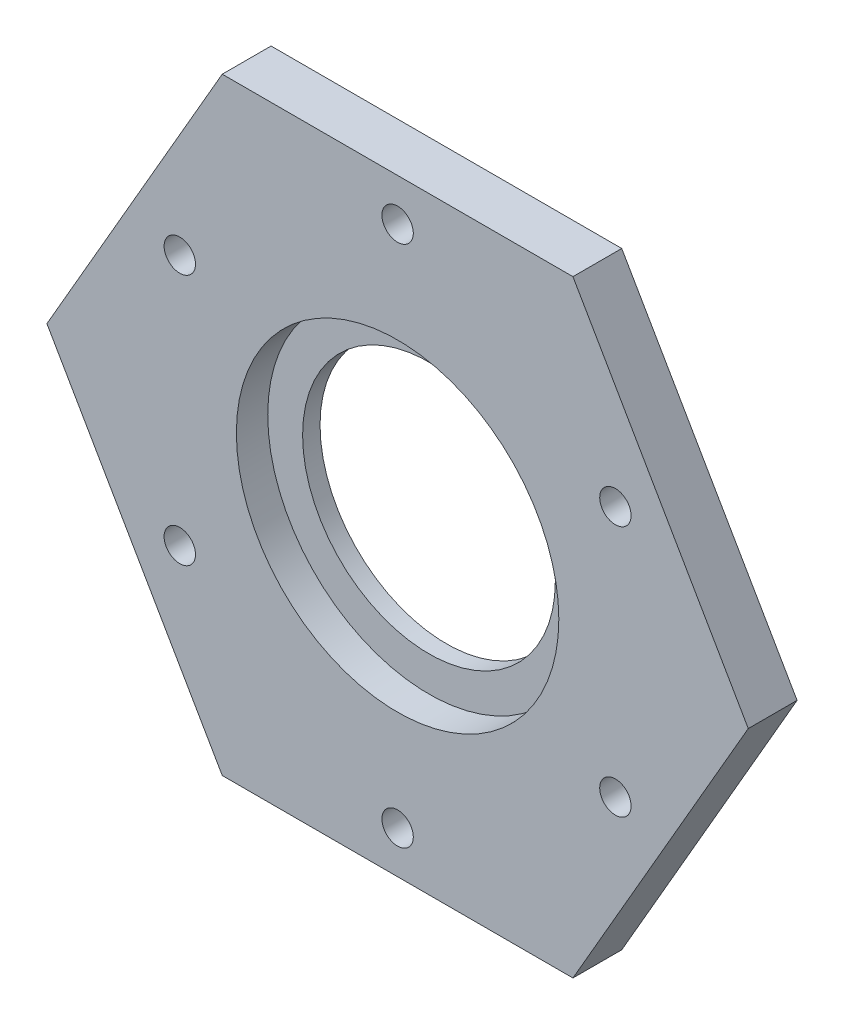
SolidWorks part; units mm, degrees
ref_plane "前视基准面" through (0, 0, 0) normal (0, 0, 1) x (1, 0, 0)
ref_plane "上视基准面" through (0, 0, 0) normal (0, 1, 0) x (1, 0, 0)
ref_plane "右视基准面" through (0, 0, 0) normal (1, 0, 0) x (0, 0, -1)
sketch "草图1" plane through (0, 0, 0) normal (0, 0, 1) x (1, 0, 0)
  line L0 (10.0594, 17.4234) -> (-10.0594, 17.4234)
  line L1 (15.5, 0) -> (7.75, 13.4234)
  line L2 (7.75, 13.4234) -> (-7.75, 13.4234)
  line L3 (-7.75, 13.4234) -> (-15.5, 0)
  line L4 (-15.5, 0) -> (-7.75, -13.4234)
  line L5 (-7.75, -13.4234) -> (7.75, -13.4234)
  line L6 (7.75, -13.4234) -> (15.5, 0)
  line L7 (-10.0594, 17.4234) -> (-20.1188, 0)
  line L8 (-20.1188, 0) -> (-10.0594, -17.4234)
  line L9 (-10.0594, -17.4234) -> (10.0594, -17.4234)
  line L10 (10.0594, -17.4234) -> (20.1188, 0)
  line L11 (20.1188, 0) -> (10.0594, 17.4234)
  circle A0 centre (0, 0) radius 13.4234 construction
  dimension "D1" = 15.5
  dimension "D2" = 4
extrude "凸台-拉伸1" add sketch "草图1" along normal blind 7
sketch "草图2" plane through (0, 0, 7) normal (0, 0, 1) x (1, 0, 0)
  line L0 (-5.5735, 13.4234) -> (-5.5735, 15.3499)
  line L1 (7.75, 13.4234) -> (-7.75, 13.4234) construction
  line L2 (-5.5735, 15.3499) -> (-4.8201, 16.0618)
  line L3 (5.5735, 13.4234) -> (5.5735, 15.3499)
  line L4 (0, 19.3164) -> (0, 10.8862) construction
  line L5 (5.5735, 15.3499) -> (4.8201, 16.0618)
  line L6 (-4.8201, 16.0618) -> (4.8201, 16.0618)
  line L7 (5.5735, 13.4234) -> (-5.5735, 13.4234)
  line L8 (0, -18.1349) -> (0, -9.4848) construction
  line L9 (6.8633, -13.4234) -> (6.8633, -16.4408)
  line L10 (-7.75, -13.4234) -> (7.75, -13.4234) construction
  line L11 (6.8633, -16.4408) -> (5.8807, -17.4234)
  line L12 (-10.0594, -17.4234) -> (10.0594, -17.4234) construction
  line L13 (-6.8633, -16.4408) -> (-5.8807, -17.4234)
  line L14 (-6.8633, -13.4234) -> (-6.8633, -16.4408)
  line L15 (-5.8807, -17.4234) -> (5.8807, -17.4234)
  line L16 (-6.8633, -13.4234) -> (6.8633, -13.4234)
  line M8 (-10.0594, -17.4234) -> (10.0594, -17.4234)
  line M12 (7.75, -13.4234) -> (-7.75, -13.4234)
extrude "切除-拉伸1" cut sketch "草图2" against normal blind 1.8 contours L14 L13 L11 L9 M12 M8 | L6 L5 L3 L7 L0 L2
sketch "草图3" plane through (0, 0, 7) normal (0, 0, 1) x (1, 0, 0)
  line L0 (8.4606, 12.1926) -> (11.9247, 14.1926)
  line L1 (15.5, 0) -> (7.75, 13.4234) construction
  line L2 (20.1188, 0) -> (10.0594, 17.4234) construction
  line L3 (11.9247, 14.1926) -> (18.4288, 2.9271)
  line L4 (18.4288, 2.9271) -> (14.9647, 0.9271)
  line L5 (14.9647, 0.9271) -> (8.4606, 12.1926)
extrude "切除-拉伸2" cut sketch "草图3" against normal blind 3
sketch "草图4" plane through (0, 0, 0) normal (0, 0, -1) x (-1, 0, 0)
  line L0 (-11.2456, -7.3688) -> (-6.3823, -7.3688)
  line L1 (-7.75, -13.4234) -> (-15.5, 0) construction
  line L2 (-6.3823, -7.3688) -> (-6.3823, -13.4234)
  line L3 (7.75, -13.4234) -> (-7.75, -13.4234) construction
  line L4 (-6.3823, -13.4234) -> (-7.75, -13.4234)
  line L5 (-7.75, -13.4234) -> (-11.2456, -7.3688)
  line L6 (6.1453, -7.3688) -> (11.2456, -7.3688)
  line L7 (15.5, 0) -> (7.75, -13.4234) construction
  line L8 (11.2456, -7.3688) -> (7.75, -13.4234)
  line L9 (7.75, -13.4234) -> (6.1453, -13.4234)
  line L10 (6.1453, -13.4234) -> (6.1453, -7.3688)
  line L11 (6.1453, 13.4234) -> (6.1453, 8.4885)
  line L12 (-7.75, 13.4234) -> (7.75, 13.4234) construction
  line L13 (6.1453, 8.4885) -> (10.5991, 8.4885)
  line L14 (7.75, 13.4234) -> (15.5, 0) construction
  line L15 (10.5991, 8.4885) -> (7.75, 13.4234)
  line L16 (7.75, 13.4234) -> (6.1453, 13.4234)
  line L17 (-8.4606, 12.1926) -> (-6.6742, 11.1612)
  line L19 (-6.6742, 11.1612) -> (-13.5028, -0.6663)
  line L20 (-13.5028, -0.6663) -> (-15.2892, 0.3651)
  line L21 (-15.5, 0) -> (-7.75, 13.4234) construction
  line L22 (-15.2892, 0.3651) -> (-8.4606, 12.1926)
extrude "凸台-拉伸4" add sketch "草图4" against normal blind 5.7 separate body
sketch "草图6" plane through (0, 0, 0) normal (0, 0, -1) x (-1, 0, 0)
  line L0 (-7.1671, 10.3074) -> (-6.1899, 10.3074)
  line L1 (-13.5028, -0.6663) -> (-6.6742, 11.1612) construction
  line L2 (-6.1899, 10.3074) -> (-6.1899, -5.9802)
  line L3 (-6.1899, -5.9802) -> (-12.0474, -5.9802)
  line L4 (-7.75, -13.4234) -> (-15.5, 0) construction
  line L7 (-15.5, 0) -> (-7.75, 13.4234) construction
  line L8 (-9.549, 10.3074) -> (-7.1671, 10.3074)
  line L9 (-5.839, 13.4234) -> (-5.839, 11.3427)
  line L10 (-7.75, 13.4234) -> (7.75, 13.4234) construction
  line L11 (-5.839, 11.3427) -> (5.7465, 11.3427)
  line L12 (5.7465, 11.3427) -> (5.7465, 13.4234)
  line L14 (6.1453, 7.2648) -> (6.1453, 3.9358)
  line L15 (6.1453, -5.9802) -> (12.0474, -5.9802)
  line L16 (15.5, 0) -> (7.75, -13.4234) construction
  line L20 (5.7465, 13.4234) -> (5.7465, 15.341)
  line L21 (5.7465, 15.341) -> (-5.839, 15.341)
  line L22 (-5.839, 15.341) -> (-5.839, 13.4234)
  line L23 (-9.549, 10.3074) -> (-11.4726, 10.3074)
  line L24 (-11.4726, 10.3074) -> (-17.3636, 0)
  line L25 (-17.3636, 0) -> (-13.6263, -5.9802)
  line L26 (-13.6263, -5.9802) -> (-12.0474, -5.9802)
  line L28 (12.8121, 7.2648) -> (14.8926, 3.9358)
  line L29 (17.3523, 0) -> (13.9344, -5.9802)
  line L30 (13.9344, -5.9802) -> (12.0474, -5.9802)
  line L31 (6.1453, 7.2648) -> (12.8121, 7.2648)
  line L32 (6.1453, 3.9358) -> (14.8926, 3.9358)
  line L33 (17.3523, 0) -> (6.1453, 0)
  line L34 (6.1453, 0) -> (6.1453, -5.9802)
extrude "凸台-拉伸21" add sketch "草图6" against normal blind 3.5 separate body
sketch "草图12" plane through (0, 0, 0) normal (0, 0, -1) x (-1, 0, 0)
  line L1 (-10.0594, 17.4234) -> (-20.1188, 0)
  line L2 (-20.1188, 0) -> (-10.0594, -17.4234)
  line L3 (-10.0594, -17.4234) -> (10.0594, -17.4234)
  line L4 (10.0594, -17.4234) -> (20.1188, 0)
  line L5 (20.1188, 0) -> (10.0594, 17.4234)
  line L6 (10.0594, 17.4234) -> (-10.0594, 17.4234)
  circle A0 centre (0, 0) radius 17.4234 construction
extrude "凸台-拉伸22" add sketch "草图12" along normal blind 1 separate body
sketch "草图13" plane through (0, 0, -1) normal (0, 0, -1) x (-1, 0, 0)
  line L0 (10.1234, 2.2395) -> (7.1359, 2.2395) construction
  line L1 (10.1234, 1.0625) -> (7.1359, 1.0625)
  line L2 (10.1234, 3.4166) -> (7.1359, 3.4166)
  line L3 (8.6297, 1.7395) -> (8.6297, 2.7395) construction
  arc A0 (10.1234, 1.0625) -> (10.1234, 3.4166) centre (10.1234, 2.2395) ccw
  arc A1 (7.1359, 3.4166) -> (7.1359, 1.0625) centre (7.1359, 2.2395) ccw
  point P2 (8.6297, 2.2395)
extrude "切除-拉伸3" cut sketch "草图13" against normal blind 10
sketch "草图14" plane through (0, 0, 5.7) normal (0, 0, 1) x (1, 0, 0)
  line L0 (-7.75, 13.4234) -> (-6.1453, 13.4234)
  line L1 (-6.1453, 13.4234) -> (-6.1453, 8.4635)
  line L2 (8.4603, 12.1924) -> (8.4603, 8.0675)
  line L3 (-7.75, 13.4234) -> (-10.5991, 8.4885)
  line L4 (-10.5991, 8.4885) -> (-6.1453, 8.4635)
  line L5 (6.6742, 11.1612) -> (8.4606, 12.1926) construction
  line L6 (13.5028, -0.6663) -> (6.6742, 11.1612) construction
  line L7 (8.4603, 8.0675) -> (6.6742, 11.1612)
  line L8 (6.6742, 11.1612) -> (8.4603, 12.1924)
extrude "切除-拉伸4" cut sketch "草图14" against normal blind 1.5
sketch "草图15" plane through (0, 0, 5.2) normal (0, 0, 1) x (1, 0, 0)
  line L0 (0, 17.0326) -> (0, 11.8468) construction
  line L1 (-2.4446, 16.0618) -> (-2.4446, 13.4234)
  line L2 (-4.8201, 16.0618) -> (4.8201, 16.0618) construction
  line L3 (5.5735, 13.4234) -> (-5.5735, 13.4234) construction
  line L4 (-2.4446, 13.4234) -> (-5.5735, 13.4234)
  line L5 (-5.5735, 13.4234) -> (-5.5735, 15.3499)
  line L6 (-5.5735, 15.3499) -> (-4.8201, 16.0618) construction
  line L7 (-5.5735, 15.3499) -> (-4.8201, 16.0618) construction
  line L8 (-5.5735, 15.3499) -> (-4.8201, 16.0618)
  line L9 (-4.8201, 16.0618) -> (-2.4446, 16.0618)
  line L10 (4.8201, 16.0618) -> (2.4446, 16.0618)
  line L11 (5.5735, 15.3499) -> (4.8201, 16.0618)
  line L12 (5.5735, 13.4234) -> (5.5735, 15.3499)
  line L13 (2.4446, 13.4234) -> (5.5735, 13.4234)
  line L14 (2.4446, 16.0618) -> (2.4446, 13.4234)
extrude "切除-拉伸5" cut sketch "草图15" against normal blind 1
sketch "草图16" plane through (0, 0, 7) normal (0, 0, 1) x (1, 0, 0)
  line L0 (7.75, 17.4234) -> (17.8094, 0)
  line L1 (10.0594, 17.4234) -> (-10.0594, 17.4234) construction
  line L2 (10.0594, -17.4234) -> (20.1188, 0) construction
  line L3 (20.1188, 0) -> (18.4288, 2.9271) construction
  line L4 (11.9247, 14.1926) -> (10.0594, 17.4234) construction
  line L5 (7.75, 17.4234) -> (10.0594, 17.4234)
  line L6 (10.0594, 17.4234) -> (20.1188, 0)
  line L7 (20.1188, 0) -> (18.9641, -2)
  line L8 (17.8094, 0) -> (7.75, -17.4234)
  line L9 (10.0594, -17.4234) -> (7.75, -17.4234)
  line L11 (18.9641, -2) -> (10.0594, -17.4234)
  line L12 (0, 18.7265) -> (0, -21.8829) construction
  line L13 (-18.9641, -2) -> (-10.0594, -17.4234)
  line L14 (-10.0594, -17.4234) -> (-7.75, -17.4234)
  line L15 (-17.8094, 0) -> (-7.75, -17.4234)
  line L16 (-20.1188, 0) -> (-18.9641, -2)
  line L17 (-10.0594, 17.4234) -> (-20.1188, 0)
  line L18 (-7.75, 17.4234) -> (-10.0594, 17.4234)
  line L19 (-7.75, 17.4234) -> (-17.8094, 0)
  dimension "D1" = 2
  dimension "D2" = 2
sketch "草图18" plane through (0, 0, 7) normal (0, 0, 1) x (1, 0, 0)
  line L0 (-4.8201, 16.0618) -> (-4.8201, 17.4234)
  line L1 (4.8201, 16.0618) -> (4.8201, 17.4234)
  line L2 (-4.8201, 17.4234) -> (-10.0594, 17.4234)
  line L9 (18.4288, 2.9271) -> (14.9647, 0.9271)
  line L10 (14.9647, 0.9271) -> (15.5, 0)
  line L11 (15.5, 0) -> (7.75, -13.4234)
  line L12 (7.75, -13.4234) -> (6.8633, -13.4234)
  line L13 (6.8633, -13.4234) -> (6.8633, -16.4408)
  line L14 (6.8633, -16.4408) -> (5.8807, -17.4234)
  line L15 (5.8807, -17.4234) -> (10.0594, -17.4234)
  line L16 (10.0594, -17.4234) -> (20.1188, 0)
  line L17 (20.1188, 0) -> (18.4288, 2.9271)
  line L18 (18.4288, 2.9271) -> (14.9647, 0.9271)
  line L19 (8.4606, 12.1926) -> (11.9247, 14.1926)
  line L20 (11.9247, 14.1926) -> (10.0594, 17.4234)
  line L21 (10.0594, 17.4234) -> (-10.0594, 17.4234)
  line L22 (-10.0594, 17.4234) -> (-20.1188, 0)
  line L23 (-20.1188, 0) -> (-10.0594, -17.4234)
  line L24 (-10.0594, -17.4234) -> (-5.8807, -17.4234)
  line L25 (-5.8807, -17.4234) -> (-6.8633, -16.4408)
  line L26 (-6.8633, -16.4408) -> (-6.8633, -13.4234)
  line L27 (-6.8633, -13.4234) -> (-7.75, -13.4234)
  line L28 (-7.75, -13.4234) -> (-15.5, 0)
  line L29 (-15.5, 0) -> (-7.75, 13.4234)
  line L30 (-7.75, 13.4234) -> (-5.5735, 13.4234)
  line L31 (-5.5735, 13.4234) -> (-5.5735, 15.3499)
  line L32 (-5.5735, 15.3499) -> (-4.8201, 16.0618)
  line L33 (-4.8201, 16.0618) -> (4.8201, 16.0618)
  line L34 (4.8201, 16.0618) -> (5.5735, 15.3499)
  line L35 (5.5735, 15.3499) -> (5.5735, 13.4234)
  line L36 (5.5735, 13.4234) -> (7.75, 13.4234)
  line L37 (7.75, 13.4234) -> (8.4606, 12.1926)
  line L38 (8.4606, 12.1926) -> (11.9247, 14.1926)
  line L39 (11.9247, 14.1926) -> (10.0594, 17.4234)
  line L40 (10.0594, 17.4234) -> (4.8201, 17.4234)
  line L41 (-10.0594, 17.4234) -> (-20.1188, 0)
  line L42 (-20.1188, 0) -> (-10.0594, -17.4234)
  line L43 (-10.0594, -17.4234) -> (-5.8807, -17.4234)
  line L44 (-5.8807, -17.4234) -> (-6.8633, -16.4408)
  line L45 (-6.8633, -16.4408) -> (-6.8633, -13.4234)
  line L46 (-6.8633, -13.4234) -> (-7.75, -13.4234)
  line L47 (-7.75, -13.4234) -> (-15.5, 0)
  line L48 (-15.5, 0) -> (-7.75, 13.4234)
  line L49 (-7.75, 13.4234) -> (-5.5735, 13.4234)
  line L50 (-5.5735, 13.4234) -> (-5.5735, 15.3499)
  line L51 (-5.5735, 15.3499) -> (-4.8201, 16.0618)
  line L53 (4.8201, 16.0618) -> (5.5735, 15.3499)
  line L54 (5.5735, 15.3499) -> (5.5735, 13.4234)
  line L55 (5.5735, 13.4234) -> (7.75, 13.4234)
  line L56 (7.75, 13.4234) -> (8.4606, 12.1926)
  line L57 (14.9647, 0.9271) -> (15.5, 0)
  line L58 (15.5, 0) -> (7.75, -13.4234)
  line L59 (7.75, -13.4234) -> (6.8633, -13.4234)
  line L60 (6.8633, -13.4234) -> (6.8633, -16.4408)
  line L61 (6.8633, -16.4408) -> (5.8807, -17.4234)
  line L62 (5.8807, -17.4234) -> (10.0594, -17.4234)
  line L63 (10.0594, -17.4234) -> (20.1188, 0)
  line L64 (20.1188, 0) -> (18.4288, 2.9271)
  dimension "D1" = 0
  dimension "D2" = 0
extrude "凸台-拉伸23" add sketch "草图18" along normal blind 1.6
sketch "草图17" plane through (0, 0, -1) normal (0, 0, -1) x (-1, 0, 0)
  line L0 (-25.1496, 0) -> (29.1565, 0) construction
  line L1 (0, -23.8718) -> (0, 23.2815) construction
  circle A0 centre (8, 15) radius 0.9
  circle A1 centre (8, -15) radius 0.9
  circle A2 centre (-8, -15) radius 0.9
  circle A3 centre (-8, 15) radius 0.9
  circle A4 centre (17.5, 0) radius 0.9
  circle A5 centre (-17.5, 0) radius 0.9
  dimension "D3" = 1.8
  dimension "D4" = 17.5
  dimension "D5" = 1.8
  dimension "D1" = 15
  dimension "D2" = 8
extrude "切除-拉伸6" cut sketch "草图17" against normal blind 20
sketch "草图19" plane through (0, 0, -1) normal (0, 0, -1) x (-1, 0, 0)
  line L0 (0, 22.8566) -> (0, -20.1355) construction
  line L1 (0, 18.7265) -> (0, -21.8829) construction
  circle A0 centre (-8, 15) radius 1.75
  circle A1 centre (-17.5, 0) radius 1.75
  circle A2 centre (-8, -15) radius 1.75
  circle A3 centre (8, -15) radius 1.75
  circle A4 centre (17.5, 0) radius 1.75
  circle A5 centre (8, 15) radius 1.75
  dimension "D1" = 3.5
extrude "切除-拉伸7" cut sketch "草图19" against normal blind 2
sketch "草图20" plane through (0, 0, -1) normal (0, 0, -1) x (-1, 0, 0)
  line L0 (-8, 15) -> (15.7821, 15) construction
  line L1 (0, 18.7265) -> (0, -21.8829) construction
  line L2 (-23.712, 0) -> (29.0686, 0) construction
  line L3 (-15.0891, 8.7117) -> (-7.0284, 4.0578) construction
  line L4 (-10.0594, 17.4234) -> (-20.1188, 0) construction
  line L5 (-8, 15) -> (-13.9005, 4.7801) construction
  line L6 (0, 10.1479) -> (0, 4.0578) construction
  circle A0 centre (0, 15) radius 0.9
  circle A1 centre (-12.4952, 7.2141) radius 0.9
  circle A2 centre (12.4952, 7.2141) radius 0.9
  circle A3 centre (-12.4952, -7.2141) radius 0.9
  circle A4 centre (12.4952, -7.2141) radius 0.9
  circle A5 centre (0, -15) radius 0.9
extrude "切除-拉伸8" cut sketch "草图20" against normal blind 6 contours A0 | A1 | A2 | A4 | A3 | A5
sketch "草图22" plane through (0, 0, -1) normal (0, 0, -1) x (-1, 0, 0)
  line L6 (10.0594, 17.4234) -> (-10.0594, 17.4234)
  line L7 (-10.0594, 17.4234) -> (-20.1188, 0)
  line L8 (-20.1188, 0) -> (-10.0594, -17.4234)
  line L9 (-10.0594, -17.4234) -> (10.0594, -17.4234)
  line L10 (10.0594, -17.4234) -> (20.1188, 0)
  line L11 (20.1188, 0) -> (10.0594, 17.4234)
  line L12 (10.0594, 17.4234) -> (-10.0594, 17.4234)
  line L13 (-10.0594, 17.4234) -> (-20.1188, 0)
  line L14 (-20.1188, 0) -> (-10.0594, -17.4234)
  line L15 (-10.0594, -17.4234) -> (10.0594, -17.4234)
  line L16 (10.0594, -17.4234) -> (20.1188, 0)
  line L17 (20.1188, 0) -> (10.0594, 17.4234)
  circle A0 centre (-12.4952, 7.2141) radius 0.9
  circle A1 centre (-12.4952, -7.2141) radius 0.9
  circle A2 centre (0, -15) radius 0.9
  circle A3 centre (12.4952, -7.2141) radius 0.9
  circle A4 centre (12.4952, 7.2141) radius 0.9
  circle A5 centre (0, 15) radius 0.9
  circle A6 centre (0, 0) radius 9.25
  dimension "D2" = 18.5
  dimension "D1" = 0
extrude "凸台-拉伸24" add sketch "草图22" along normal blind 2.8
sketch "草图24" plane through (0, 0, -3.8) normal (0, 0, -1) x (-1, 0, 0)
  circle A0 centre (0, 0) radius 9.25
  circle A1 centre (0, 0) radius 7.25
  dimension "D1" = 14.5
extrude "凸台-拉伸25" add sketch "草图24" against normal blind 1
sketch "草图25" plane through (0, -17.4234, 0) normal (0, -1, 0) x (1, 0, 0)
  line L0 (10.0594, -1) -> (20.1188, -1) construction
  line L5 (20.1188, -1) -> (-23.1529, -1)
  line L6 (20.1188, -1) -> (20.1188, 16.1109)
  line L7 (20.1188, 16.1109) -> (-23.1529, 16.1109)
  line L8 (-23.1529, -1) -> (-23.1529, 16.1109)
extrude "切除-拉伸9" cut sketch "草图25" against normal blind 47
sketch "草图26" plane through (-15.0891, -8.7117, 0) normal (-0.866, -0.5, 0) x (0, 0, 1)
  line L1 (-1, -20.7071) -> (19.8122, -20.7071)
  line L2 (-1, -20.7071) -> (-1, 32.4398)
  line L3 (-1, 32.4398) -> (19.8122, 32.4398)
  line L4 (19.8122, -20.7071) -> (19.8122, 32.4398)
extrude "切除-拉伸10" cut sketch "草图26" against normal blind 99
